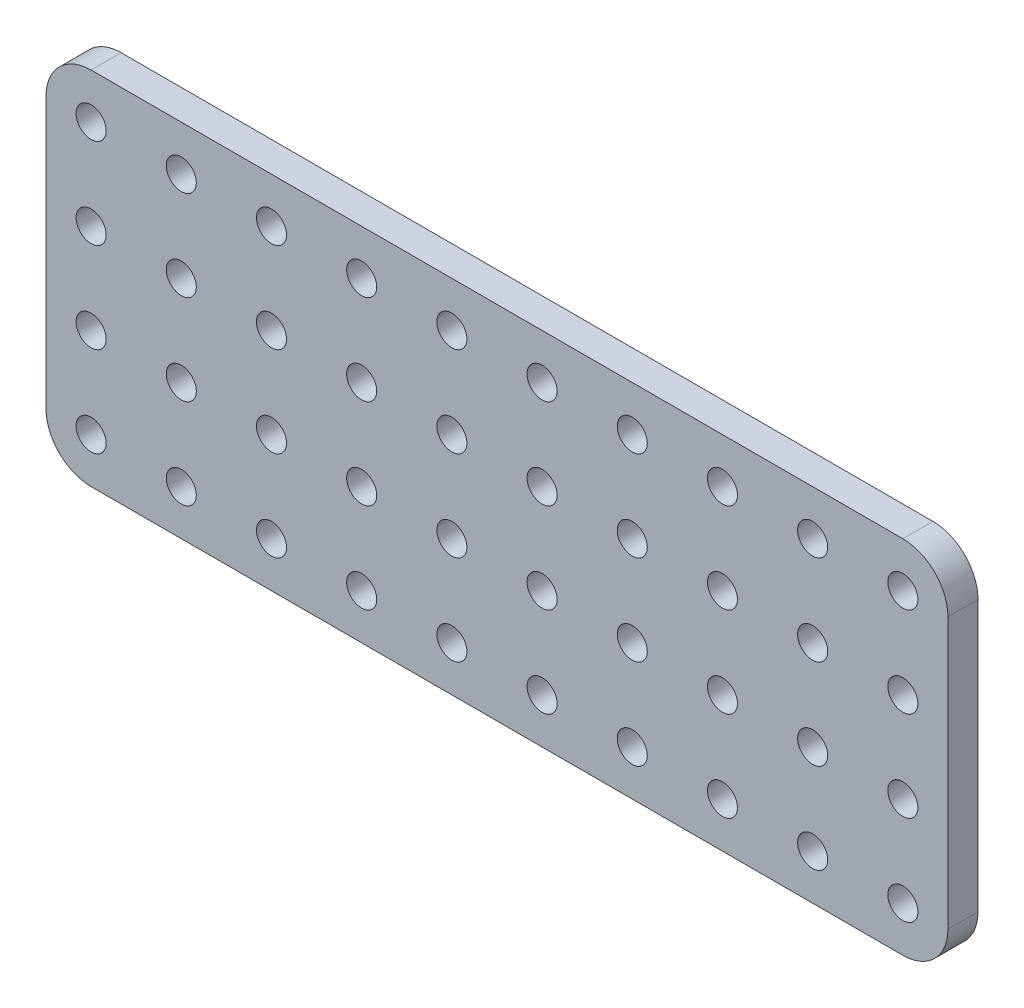
SolidWorks part; units mm, degrees
ref_plane "Alzado" through (0, 0, 0) normal (0, 0, 1) x (1, 0, 0)
ref_plane "Planta" through (0, 0, 0) normal (0, 1, 0) x (1, 0, 0)
ref_plane "Vista lateral" through (0, 0, 0) normal (1, 0, 0) x (0, 0, -1)
sketch "Model" plane through (0, 0, 0) normal (0, 0, 1) x (1, 0, 0)
  line L0 (-105.9434, 101.0565) -> (-105.9434, 74.0565)
  line L1 (-101.4434, 69.5565) -> (-20.4434, 69.5565)
  line L2 (-20.4434, 105.5565) -> (-101.4434, 105.5565)
  line L3 (-15.9434, 74.0565) -> (-15.9434, 101.0565)
  circle A0 centre (-101.4434, 101.0565) radius 1.5
  circle A1 centre (-92.4434, 101.0565) radius 1.5
  circle A2 centre (-83.4434, 101.0565) radius 1.5
  circle A3 centre (-74.4434, 101.0565) radius 1.5
  circle A4 centre (-65.4434, 101.0565) radius 1.5
  circle A5 centre (-56.4434, 101.0565) radius 1.5
  circle A6 centre (-47.4434, 101.0565) radius 1.5
  circle A7 centre (-38.4434, 101.0565) radius 1.5
  circle A8 centre (-101.4434, 92.0565) radius 1.5
  circle A9 centre (-92.4434, 92.0565) radius 1.5
  circle A10 centre (-83.4434, 92.0565) radius 1.5
  circle A11 centre (-74.4434, 92.0565) radius 1.5
  circle A12 centre (-65.4434, 92.0565) radius 1.5
  circle A13 centre (-56.4434, 92.0565) radius 1.5
  circle A14 centre (-47.4434, 92.0565) radius 1.5
  circle A15 centre (-38.4434, 92.0565) radius 1.5
  circle A16 centre (-101.4434, 83.0565) radius 1.5
  circle A17 centre (-92.4434, 83.0565) radius 1.5
  circle A18 centre (-83.4434, 83.0565) radius 1.5
  circle A19 centre (-74.4434, 83.0565) radius 1.5
  circle A20 centre (-65.4434, 83.0565) radius 1.5
  circle A21 centre (-56.4434, 83.0565) radius 1.5
  circle A22 centre (-47.4434, 83.0565) radius 1.5
  circle A23 centre (-38.4434, 83.0565) radius 1.5
  circle A24 centre (-101.4434, 74.0565) radius 1.5
  circle A25 centre (-92.4434, 74.0565) radius 1.5
  circle A26 centre (-83.4434, 74.0565) radius 1.5
  circle A27 centre (-74.4434, 74.0565) radius 1.5
  circle A28 centre (-65.4434, 74.0565) radius 1.5
  circle A29 centre (-56.4434, 74.0565) radius 1.5
  circle A30 centre (-47.4434, 74.0565) radius 1.5
  circle A31 centre (-38.4434, 74.0565) radius 1.5
  arc A32 (-101.4434, 105.5565) -> (-105.9434, 101.0565) centre (-101.4434, 101.0565) ccw
  arc A33 (-105.9434, 74.0565) -> (-101.4434, 69.5565) centre (-101.4434, 74.0565) ccw
  circle A34 centre (-29.4434, 101.0565) radius 1.5
  circle A35 centre (-29.4434, 92.0565) radius 1.5
  circle A36 centre (-29.4434, 83.0565) radius 1.5
  circle A37 centre (-29.4434, 74.0565) radius 1.5
  arc A38 (-15.9434, 101.0565) -> (-20.4434, 105.5565) centre (-20.4434, 101.0565) ccw
  arc A39 (-20.4434, 69.5565) -> (-15.9434, 74.0565) centre (-20.4434, 74.0565) ccw
  circle A40 centre (-20.4434, 101.0565) radius 1.5
  circle A41 centre (-20.4434, 92.0565) radius 1.5
  circle A42 centre (-20.4434, 83.0565) radius 1.5
  circle A43 centre (-20.4434, 74.0565) radius 1.5
extrude "Saliente-Extruir1" add sketch "Model" along normal blind 3
